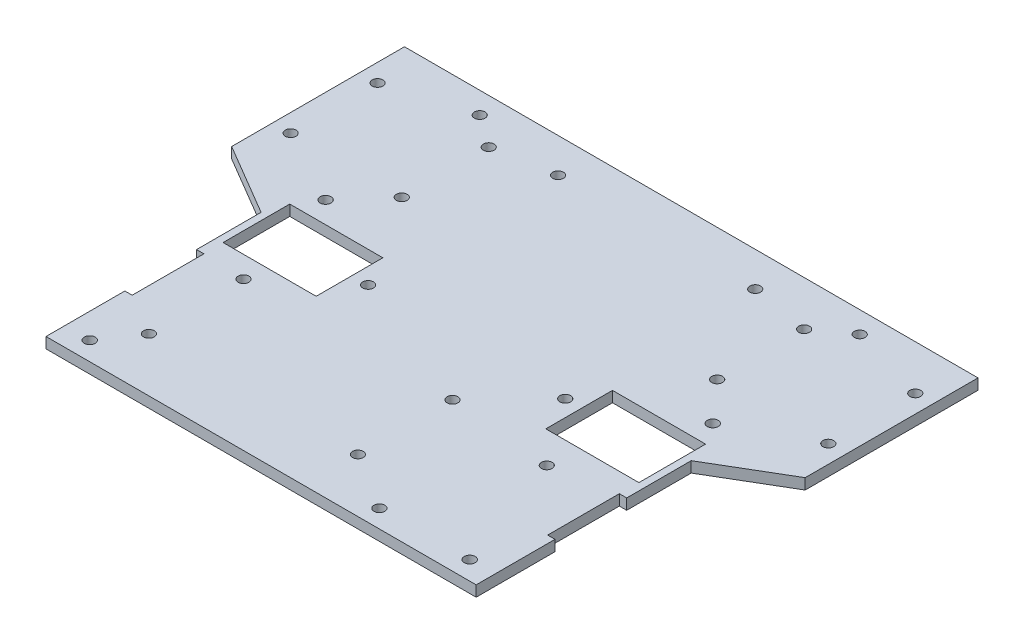
SolidWorks part; units mm, degrees
material "Perspex (TM) GS Acrylic Cast Sheet"
ref_plane "Front Plane" through (0, 0, 0) normal (0, 0, 1) x (1, 0, 0)
ref_plane "Top Plane" through (0, 0, 0) normal (0, 1, 0) x (1, 0, 0)
ref_plane "Right Plane" through (0, 0, 0) normal (1, 0, 0) x (0, 0, -1)
sketch "Sketch1" plane through (0, 0, 0) normal (0, 1, 0) x (1, 0, 0)
  line L0 (-60, 0) -> (-80, 11.7918)
  line L1 (60, -60) -> (-60, -60)
  line L2 (60, -60) -> (60, 60)
  line L3 (60, 60) -> (-60, 60)
  line L4 (-60, -60) -> (-60, 60)
  line L5 (60, -60) -> (-60, 60) construction
  line L6 (60, 60) -> (-60, -60) construction
  line L7 (-80, 11.7918) -> (-80, 60)
  line L8 (-80, 60) -> (-60, 60)
  line L9 (0, 0) -> (0, 60) construction
  line L10 (60, 0) -> (80, 11.7918)
  line L11 (80, 60) -> (60, 60)
  line L12 (80, 11.7918) -> (80, 60)
  point P0 (0, 0)
  dimension "D1" = 120
  dimension "D2" = 120
  dimension "D3" = 20
  dimension "D4" = 30.523
  dimension "D5" = 60
extrude "Boss-Extrude1" add sketch "Sketch1" along normal blind 3 contours L4 L1 L2 L3 | L8 L7 L0 L4 | L10 L12 L11 L2
sketch "Sketch2" plane through (0, 3, 0) normal (0, 1, 0) x (1, 0, 0)
  line L0 (60, -60) -> (60, 0) construction
  line L1 (-60, -60) -> (-60, 0) construction
  line L3 (60, -60) -> (-60, -60) construction
  circle A0 centre (28, -55) radius 1.5
  circle A1 centre (41, -21.3005) radius 1.5
  circle A2 centre (-46.29, -45) radius 1.5
  circle A3 centre (12, -45) radius 1.5
  circle A4 centre (-46.29, -18.6) radius 1.5
  circle A5 centre (12, -18.6) radius 1.5
  dimension "D1" = 3
  dimension "D2" = 36.12
  dimension "D3" = 5
  dimension "D4" = 3
  dimension "D6" = 3
  dimension "D7" = 3
  dimension "D11" = 48
  dimension "D12" = 3
  dimension "D13" = 3
  dimension "12.6" = 13
  dimension "D8" = 58.29
  dimension "D10" = 15
  dimension "26.4" = 26.4
  dimension "D15" = 26.4
  dimension "D16" = 58.29
  dimension "D17" = 48
  dimension "D18" = 88
extrude "Cut-Extrude1" cut sketch "Sketch2" against normal through all
sketch "Sketch3" plane through (0, 3, 0) normal (0, 1, 0) x (1, 0, 0)
  line L0 (-0.0296, 57.8856) -> (-0.0296, -0.1144) construction
  line L1 (-30.0296, 23.8856) -> (29.9704, 23.8856) construction
  line L4 (-80, 11.7918) -> (-80, 60) construction
  line L6 (-80, 11.7918) -> (-80, 60) construction
  line L7 (80, 60) -> (-80, 60) construction
  line L8 (-60, 0) -> (-60, 60) construction
  line L9 (60, 0) -> (60, 60) construction
  circle A0 centre (-27.5296, 50.3856) radius 1.5
  circle A1 centre (-27.5296, -2.6144) radius 1.5
  circle A2 centre (27.4704, -2.6144) radius 1.5
  circle A3 centre (27.4704, 50.3856) radius 1.5
  point P16 (-80, 35.8959)
  dimension "D1" = 52.4704
  dimension "D2" = 36.1144
  dimension "D3" = 3
  dimension "D4" = 79.9704
  dimension "D5" = 26.5
extrude "Cut-Extrude3" cut sketch "Sketch3" against normal through all
sketch "Sketch4" plane through (0, 3, 0) normal (0, 1, 0) x (1, 0, 0)
  line L0 (-59.5, 57.5) -> (-59.5, 31.5) construction
  line L1 (-80, 11.7918) -> (-80, 60) construction
  line L2 (80, 60) -> (-80, 60) construction
  line L3 (0, 0) -> (0, 60) construction
  circle A0 centre (-75, 23.24) radius 1.5
  circle A1 centre (-75, 47.5) radius 1.5
  circle A2 centre (-44, 23.24) radius 1.5
  circle A3 centre (-44, 47.5) radius 1.5
  circle A4 centre (44, 47.5) radius 1.5
  circle A5 centre (44, 23.24) radius 1.5
  circle A6 centre (75, 23.24) radius 1.5
  circle A7 centre (75, 47.5) radius 1.5
  dimension "D1" = 3
  dimension "D2" = 3
  dimension "D5" = 5
  dimension "D6" = 12.5
  dimension "D7" = 5
  dimension "D3" = 24.26
  dimension "D4" = 15.5
extrude "Cut-Extrude4" cut sketch "Sketch4" against normal through all
sketch "Sketch6" plane through (0, 3, 0) normal (0, 1, 0) x (1, 0, 0)
  line L0 (60, -60) -> (-60, -60) construction
  line L7 (-60, -60) -> (-60, 0) construction
  line L8 (0, 0) -> (0, -60) construction
  line L23 (-60, -30) -> (60, -30) construction
  line L24 (60, -60) -> (60, 0) construction
  circle A0 centre (-53, -54.8) radius 1.525
  circle A1 centre (53, -54.8) radius 1.525
  circle A2 centre (-54, 12.0025) radius 1.525
  circle A3 centre (54, 12.0025) radius 1.525
  dimension "D9" = 7
  dimension "D11" = 3.05
  dimension "D2" = 66.81
  dimension "D3" = 6
  dimension "D10" = 5.2
extrude "Cut-Extrude7" cut sketch "Sketch6" against normal through all
sketch "Sketch10" plane through (0, 3, 0) normal (0, 1, 0) x (1, 0, 0)
  line L1 (-32.0296, -12.6) -> (-58, -12.6)
  line L2 (-32.0296, -12.6) -> (-32.0296, 6.0025)
  line L3 (-32.0296, 6.0025) -> (-58, 6.0025)
  line L4 (-58, -12.6) -> (-58, 6.0025)
  line L5 (-32.0296, -12.6) -> (-58, 6.0025) construction
  line L6 (-32.0296, 6.0025) -> (-58, -12.6) construction
  line L10 (-60, -60) -> (-60, 0) construction
  line L11 (0, 0) -> (0, -26.6372) construction
  line L12 (32.0296, 6.0025) -> (58, -12.6) construction
  line L13 (32.0296, -12.6) -> (58, 6.0025) construction
  line L14 (58, -12.6) -> (58, 6.0025)
  line L15 (32.0296, 6.0025) -> (58, 6.0025)
  line L16 (32.0296, -12.6) -> (32.0296, 6.0025)
  line L17 (32.0296, -12.6) -> (58, -12.6)
  circle A1 centre (-27.5296, -2.6144) radius 1.5 construction
  circle A2 centre (-46.29, -18.6) radius 1.5 construction
  circle A3 centre (-54, 12.0025) radius 1.525 construction
  point P0 (-45.0148, -3.2987)
  point P10 (45.0148, -3.2987)
  dimension "D1" = 4.5
  dimension "D2" = 2
  dimension "D3" = 6
  dimension "D4" = 6
extrude "Cut-Extrude9" cut sketch "Sketch10" against normal blind 5
sketch "Sketch11" plane through (0, 3, 0) normal (0, 1, 0) x (1, 0, 0)
  line L0 (80, 60) -> (-80, 60) construction
  line L1 (0, 0) -> (0, 60) construction
  line L2 (-80, 11.7918) -> (-80, 60) construction
  circle A0 centre (-53, 54) radius 1.5
  circle A1 centre (53, 54) radius 1.5
  dimension "D1" = 3
  dimension "D3" = 27
  dimension "D2" = 6
extrude "Cut-Extrude10" cut sketch "Sketch11" against normal blind 5
sketch "Sketch12" plane through (0, 3, 0) normal (0, 1, 0) x (1, 0, 0)
  line L0 (80, 60) -> (-80, 60) construction
  line L1 (-60, -18) -> (-57.95, -18)
  line L2 (-60, -18) -> (-60, -38)
  line L3 (-60, -38) -> (-57.95, -38)
  line L4 (-57.95, -18) -> (-57.95, -38)
  line L5 (-60, -18) -> (-57.95, -38) construction
  line L6 (-60, -38) -> (-57.95, -18) construction
  line L13 (-60, -60) -> (-60, 0) construction
  line L14 (60, -60) -> (-60, -60) construction
  line L15 (0, 0) -> (0, -60) construction
  line L20 (57.95, -18) -> (57.95, -38)
  line L21 (60, -38) -> (57.95, -38)
  line L22 (60, -18) -> (60, -38)
  line L23 (60, -18) -> (57.95, -18)
  point P0 (-58.975, -28)
  dimension "D1" = 20
  dimension "D2" = 78
  dimension "D3" = 2.05
  dimension "D4" = 0
extrude "Cut-Extrude11" cut sketch "Sketch12" against normal blind 10
